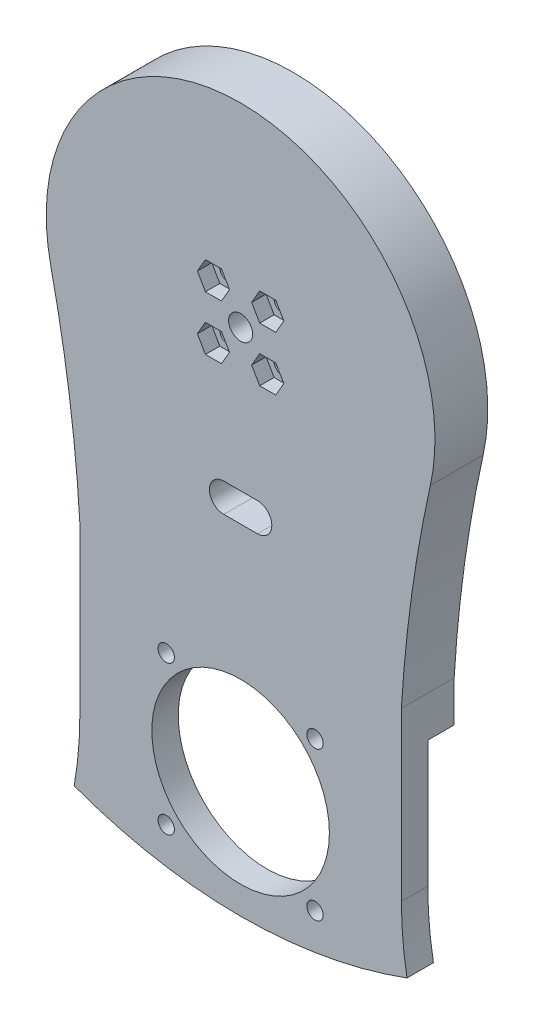
SolidWorks part; units mm, degrees
ref_plane "Front Plane" through (0, 0, 0) normal (0, 0, 1) x (1, 0, 0)
ref_plane "Top Plane" through (0, 0, 0) normal (0, 1, 0) x (1, 0, 0)
ref_plane "Right Plane" through (0, 0, 0) normal (1, 0, 0) x (0, 0, -1)
sketch "Sketch1" plane through (0, 0, 0) normal (0, 0, 1) x (1, 0, 0)
  line L0 (-79.9282, -98) -> (79.9282, -98) construction
  line L1 (-21.5, 21.5) -> (21.5, 21.5)
  line L2 (-21.5, 21.5) -> (-21.5, -21.5)
  line L3 (-21.5, -21.5) -> (21.5, -21.5)
  line L4 (21.5, 21.5) -> (21.5, -21.5)
  line L5 (-21.5, 21.5) -> (21.5, -21.5) construction
  line L6 (-21.5, -21.5) -> (21.5, 21.5) construction
  line L7 (-33.5, 21.5) -> (33.5, 21.5)
  line L8 (-33.5, 21.5) -> (-33.5, -31.5)
  line L9 (-33.5, -31.5) -> (33.5, -31.5)
  line L10 (33.5, 21.5) -> (33.5, -31.5)
  line L11 (-33.5, 21.5) -> (33.5, -31.5) construction
  line L12 (-33.5, -31.5) -> (33.5, 21.5) construction
  line L13 (-59.5091, 0) -> (49.588, 0) construction
  line L14 (0, -98) -> (-73.46, -24.54) construction
  line L15 (0, -98) -> (0, 0) construction
  line L16 (0, -98) -> (73.46, -24.54) construction
  line L17 (-51.5944, -53.7053) -> (51.5944, -53.7053)
  line L18 (0, -98) -> (0, 62) construction
  line L19 (0, 62) -> (0, 86) construction
  line L20 (-33.5, -31.5) -> (-38.3942, -31.5)
  line L21 (33.5, -31.5) -> (38.3942, -31.5)
  line L22 (-33.5, -30) -> (33.5, -30)
  line L23 (33.5, -30) -> (37.8422, -30)
  line L24 (-33.5, -30) -> (-37.8422, -30)
  circle A2 centre (-33.5, 0) radius 2.5982 construction
  circle A3 centre (-48.0833, -49.9167) radius 10.7942 construction
  circle A4 centre (48.0833, -49.9167) radius 10.7942 construction
  circle A5 centre (33.5, 0) radius 2.5982 construction
  arc A6 (-51.5944, -53.7053) -> (-33.5, -4.8509) centre (-108.5, -4.8509) ccw
  circle A7 centre (0, -98) radius 34.0704
  circle A8 centre (0, -98) radius 68
  arc A9 (51.5944, -53.7053) -> (33.5, -4.8509) centre (108.5, -4.8509) cw
  circle A10 centre (0, 0) radius 18.5
  point P0 (0, 0)
  point P6 (0, -5)
  point P38 (0, -98)
  dimension "D6" = 136
  dimension "D7" = 68.1408
  dimension "D10" = 75
  dimension "D11" = 75
  dimension "D13" = 37
  dimension "D1" = 43
  dimension "D2" = 43
  dimension "D3" = 53
  dimension "D4" = 10
  dimension "D5" = 12
  dimension "D8" = 26.3509
  dimension "D9" = 26.3509
  dimension "D12" = 103.1888
  dimension "D14" = 18.4167
  dimension "D15" = 14.5833
  dimension "D16" = 14.5833
  dimension "D17" = 18.4167
  dimension "D18" = 22.2053
  dimension "D19" = 159.8564
  dimension "D20" = 103.8881
  dimension "D21" = 103.8881
  dimension "D22" = 160
  dimension "D23" = 62
  dimension "D24" = 184
extrude "Boss-Extrude1" add sketch "Sketch1" along normal blind 5.5 contours A6 L24 L8 | L8 L22 L10 L7 L4 L3 L2 | L23 A9 L10 | L4 L1 L2 L3 A10 | A8 A9 L21 L9 | A8 L9 L20 A6 | A8 L22 L8 L9 | A8 L9 L10 L22 | L21 A9 L23 L10 | A6 L20 L8 L24
sketch "Sketch2" plane through (0, 0, 5.5) normal (0, 0, 1) x (1, 0, 0)
  line L0 (0, 0) -> (0, 82) construction
  line L1 (-33.5, 21.5) -> (33.5, 21.5)
  line L2 (33.5, 21.5) -> (33.5, 30)
  line L3 (33.5, 30) -> (-33.5, 30)
  line L4 (-33.5, 21.5) -> (-33.5, 30)
  line L5 (-8, 82) -> (8, 82) construction
  line L6 (-5.6569, 87.6569) -> (0, 82)
  line L7 (-5.6569, 76.3431) -> (0, 82) construction
  line L8 (0, 82) -> (5.6569, 87.6569) construction
  line L9 (0, 82) -> (5.6569, 76.3431) construction
  circle A0 centre (0, 0) radius 18.5 construction
  circle A1 centre (0, -98) radius 68 construction
  circle A2 centre (0, 82) radius 2.5
  circle A3 centre (0, 82) radius 8 construction
  circle A4 centre (0, 82) radius 40.5
  circle A5 centre (0, 0) radius 27.5 construction
  arc A6 (-33.5, 30) -> (-39.5426, 73.2458) centre (-309.506, 13.4799) ccw
  circle A7 centre (0, 82) radius 40 construction
  arc A8 (33.5, 30) -> (39.5426, 73.2458) centre (309.506, 13.4799) cw
  circle A14 centre (-5.6569, 87.6569) radius 1.7
  circle A15 centre (5.6569, 87.6569) radius 1.7
  circle A16 centre (5.6569, 76.3431) radius 1.7
  circle A17 centre (-5.6569, 76.3431) radius 1.7
  line M4 (33.5, 21.5) -> (-33.5, 21.5)
  dimension "D3" = 136
  dimension "D4" = 37
  dimension "D5" = 5
  dimension "D6" = 16
  dimension "D7" = 81
  dimension "D8" = 55
  dimension "D9" = 30
  dimension "D10" = 80
  dimension "D11" = 553
  dimension "D12" = 276.5
  dimension "D13" = 45
  dimension "D14" = 3.4
  dimension "D15" = 3.4
  dimension "D16" = 3.4
  dimension "D17" = 3.4
  dimension "D1" = 98
  dimension "D2" = 180
  dimension "D18" = 45
  dimension "D19" = 45
  dimension "D20" = 45
extrude "Boss-Extrude2" add sketch "Sketch2" against normal blind 11 contours L3 A8 A4 A6 | L4 L2 L3 M4 | A4 A2
sketch "Sketch3" plane through (0, 0, 5.5) normal (0, 0, 1) x (1, 0, 0)
  line L1 (-15.5, -15.5) -> (15.5, -15.5) construction
  line L2 (-15.5, -15.5) -> (-15.5, 15.5) construction
  line L3 (-15.5, 15.5) -> (15.5, 15.5) construction
  line L4 (15.5, -15.5) -> (15.5, 15.5) construction
  line L5 (-15.5, -15.5) -> (15.5, 15.5) construction
  line L6 (-15.5, 15.5) -> (15.5, -15.5) construction
  circle A0 centre (-15.5, 15.5) radius 1.7
  circle A1 centre (15.5, 15.5) radius 1.7
  circle A2 centre (15.5, -15.5) radius 1.7
  circle A3 centre (-15.5, -15.5) radius 1.7
  point P0 (0, 0)
  point P16 (0, 0)
  dimension "D3" = 3.4
  dimension "D1" = 31
  dimension "D2" = 31
  dimension "D4" = 4
extrude "Cut-Extrude1" cut sketch "Sketch3" against normal through all contours A3 | A2 | A1 | A0
sketch "Sketch4" plane through (0, 0, 0) normal (0, 0, -1) x (-1, 0, 0)
  line L0 (-33.5, 21.5) -> (33.5, 21.5) construction
  line L1 (-33.5, 21.5) -> (-33.5, -18.5) construction
  line L2 (33.5, 21.5) -> (33.5, -18.5) construction
  line L3 (-33.5, -18.5) -> (33.5, -18.5) construction
  line L4 (-33.5, -18.5) -> (33.5, -18.5)
  line L5 (-65, -0.2716) -> (-65, -64.2716)
  line L6 (-65, -64.2716) -> (65, -64.2716)
  line L7 (65, -0.2716) -> (65, -64.2716)
  circle A0 centre (0, 0) radius 18.5
  arc A1 (-65, -0.2716) -> (65, -0.2716) centre (0, 75.7218) ccw
  arc M14 (51.5944, -53.7053) -> (33.5, -4.8509) centre (108.5, -4.8509) cw
  arc M18 (-33.5, -4.8509) -> (-51.5944, -53.7053) centre (-108.5, -4.8509) cw
  arc M19 (-51.5944, -53.7053) -> (51.5944, -53.7053) centre (0, -98) cw
  dimension "D2" = 200
  dimension "D3" = 100
  dimension "D6" = 37
  dimension "D1" = 40
  dimension "D4" = 64
  dimension "D5" = 130
  dimension "D7" = 64
extrude "Cut-Extrude11" cut sketch "Sketch4" against normal blind 10 contours A1 M18 M19 M14
sketch "Sketch5" plane through (0, 0, 5.5) normal (0, 0, 1) x (1, 0, 0)
  line L0 (-7.3319, 90.558) -> (-3.9819, 84.7557) construction
  line L1 (-7.3319, 84.7557) -> (-3.9819, 90.558) construction
  line L2 (-9.0069, 87.6569) -> (-2.3069, 87.6569) construction
  line L3 (2.3069, 87.6569) -> (9.0069, 87.6569) construction
  line L4 (-9.0069, 76.3431) -> (-2.3069, 76.3431) construction
  line L5 (2.3069, 76.3431) -> (9.0069, 76.3431) construction
  line L6 (3.9819, 90.558) -> (7.3319, 84.7557) construction
  line L7 (3.9819, 84.7557) -> (7.3319, 90.558) construction
  line L8 (3.9819, 79.2443) -> (7.3319, 73.442) construction
  line L9 (3.9819, 73.442) -> (7.3319, 79.2443) construction
  line L10 (-7.3319, 79.2443) -> (-3.9819, 73.442) construction
  line L11 (-7.3319, 73.442) -> (-3.9819, 79.2443) construction
  line L12 (-7.3319, 90.558) -> (-3.9819, 90.558)
  line L13 (-3.9819, 90.558) -> (-2.3069, 87.6569)
  line L14 (-2.3069, 87.6569) -> (-3.9819, 84.7557)
  line L15 (-3.9819, 84.7557) -> (-7.3319, 84.7557)
  line L16 (-7.3319, 84.7557) -> (-9.0069, 87.6569)
  line L17 (-9.0069, 87.6569) -> (-7.3319, 90.558)
  line L18 (3.9819, 90.558) -> (7.3319, 90.558)
  line L19 (7.3319, 90.558) -> (9.0069, 87.6569)
  line L20 (9.0069, 87.6569) -> (7.3319, 84.7557)
  line L21 (7.3319, 84.7557) -> (3.9819, 84.7557)
  line L22 (3.9819, 84.7557) -> (2.3069, 87.6569)
  line L23 (2.3069, 87.6569) -> (3.9819, 90.558)
  line L24 (-7.3319, 79.2443) -> (-9.0069, 76.3431)
  line L25 (-9.0069, 76.3431) -> (-7.3319, 73.442)
  line L26 (-7.3319, 73.442) -> (-3.9819, 73.442)
  line L27 (-3.9819, 73.442) -> (-2.3069, 76.3431)
  line L28 (-2.3069, 76.3431) -> (-3.9819, 79.2443)
  line L29 (-3.9819, 79.2443) -> (-7.3319, 79.2443)
  line L30 (3.9819, 79.2443) -> (7.3319, 79.2443)
  line L31 (7.3319, 79.2443) -> (9.0069, 76.3431)
  line L32 (9.0069, 76.3431) -> (7.3319, 73.442)
  line L33 (7.3319, 73.442) -> (3.9819, 73.442)
  line L34 (3.9819, 73.442) -> (2.3069, 76.3431)
  line L35 (2.3069, 76.3431) -> (3.9819, 79.2443)
  circle A0 centre (-5.6569, 87.6569) radius 3.35 construction
  circle A1 centre (5.6569, 87.6569) radius 3.35 construction
  circle A2 centre (5.6569, 76.3431) radius 3.35 construction
  circle A3 centre (-5.6569, 76.3431) radius 3.35 construction
  dimension "D1" = 6.7
  dimension "D2" = 6.7
  dimension "D3" = 6.7
  dimension "D4" = 6.7
  dimension "D5" = 60
  dimension "D6" = 60
  dimension "D7" = 60
  dimension "D8" = 60
  dimension "D9" = 60
  dimension "D10" = 60
  dimension "D11" = 60
  dimension "D12" = 60
extrude "Cut-Extrude12" cut sketch "Sketch5" against normal blind 3
sketch "Sketch6" plane through (0, 0, -5.5) normal (0, 0, -1) x (-1, 0, 0)
  line L0 (3.5, 49.5) -> (-3.5, 49.5) construction
  line L1 (3.5, 46.5) -> (-3.5, 46.5)
  line L2 (3.5, 52.5) -> (-3.5, 52.5)
  line L3 (-33.5, 21.5) -> (33.5, 21.5) construction
  arc A0 (3.5, 46.5) -> (3.5, 52.5) centre (3.5, 49.5) ccw
  arc A1 (-3.5, 52.5) -> (-3.5, 46.5) centre (-3.5, 49.5) ccw
  point P2 (0, 49.5)
  dimension "D1" = 3
  dimension "D2" = 7
  dimension "D3" = 28
extrude "Cut-Extrude13" cut sketch "Sketch6" against normal through all
